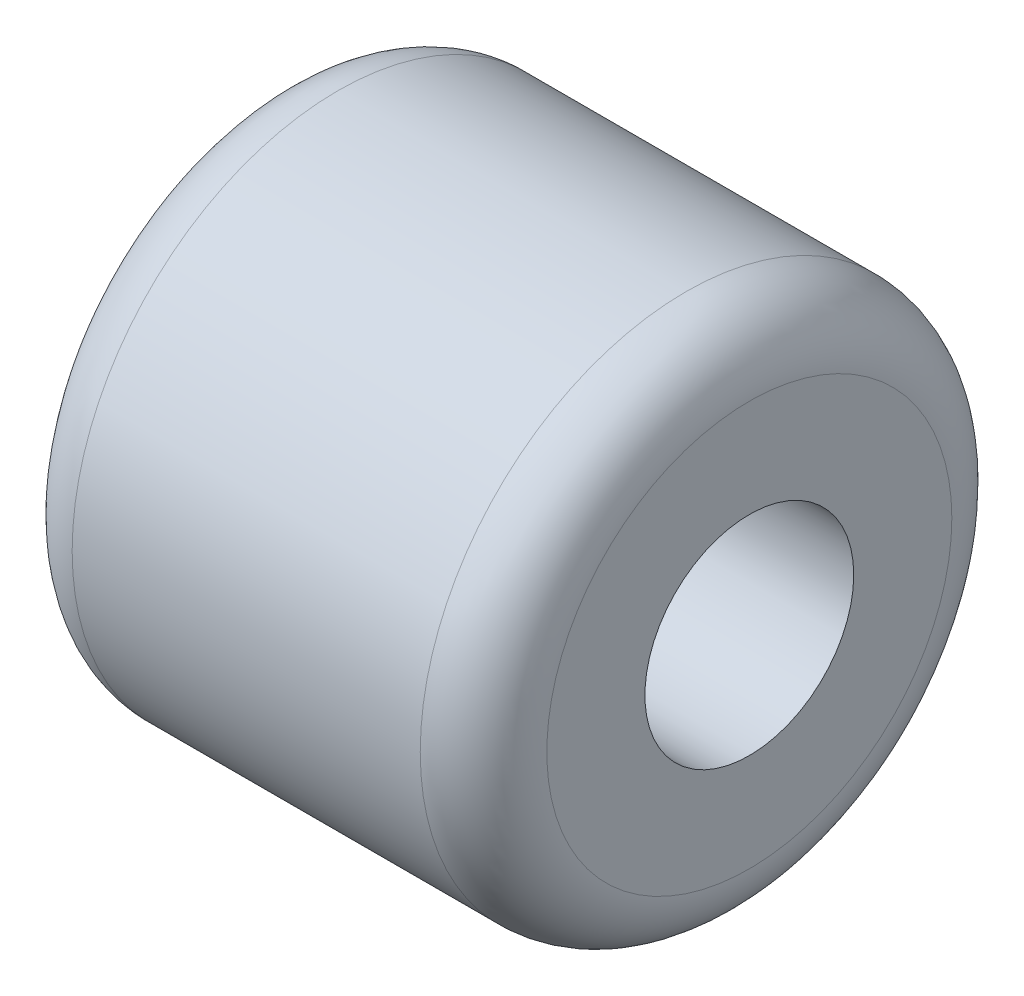
SolidWorks part; units mm, degrees
ref_plane "前视基准面" through (0, 0, 0) normal (0, 0, 1) x (1, 0, 0)
ref_plane "上视基准面" through (0, 0, 0) normal (0, 1, 0) x (1, 0, 0)
ref_plane "右视基准面" through (0, 0, 0) normal (1, 0, 0) x (0, 0, -1)
sketch "草图1" plane through (0, 0, 0) normal (1, 0, 0) x (0, 0, -1)
  circle A0 centre (0, 0) radius 8.4
  dimension "D1" = 16.8
extrude "凸台-拉伸1" add sketch "草图1" along normal mid plane 15
sketch "草图2" plane through (7.5, 0, 0) normal (1, 0, 0) x (0, 0, -1)
  circle A0 centre (0, 0) radius 3.3
  circle A1 centre (0, 0) radius 8.4 construction
  dimension "D1" = 5.1
extrude "切除-拉伸1" cut sketch "草图2" against normal blind 15
fillet "圆角1" radius 2 2 edges at (-7.5, 0, -8.4) (7.5, 0, -8.4)
